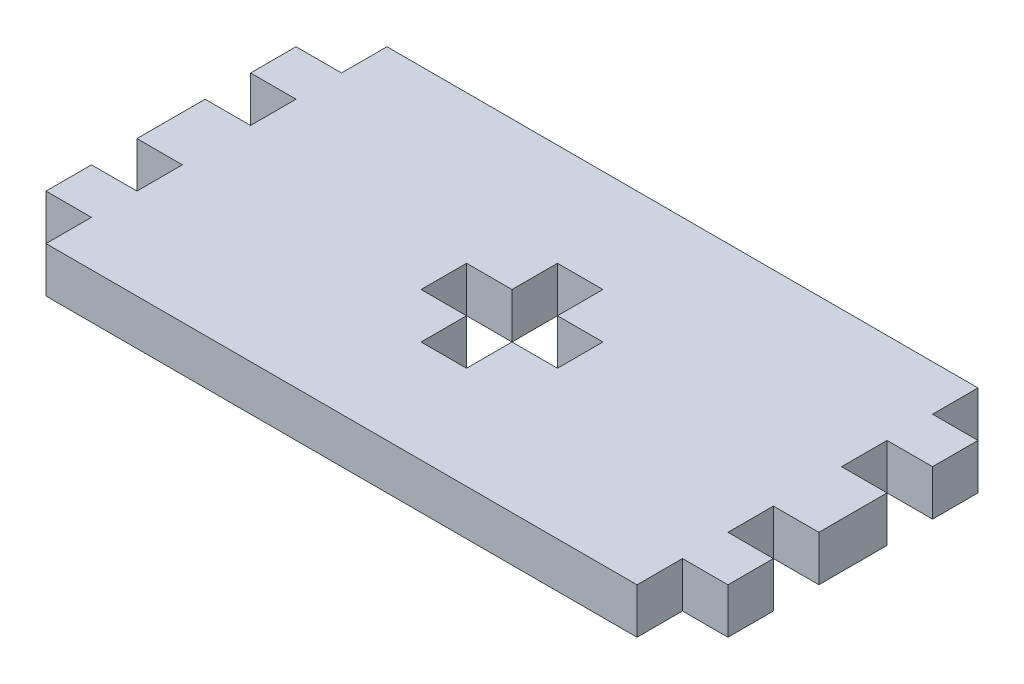
SolidWorks part; units mm, degrees
ref_plane "Front Plane" through (0, 0, 0) normal (0, 0, 1) x (1, 0, 0)
ref_plane "Top Plane" through (0, 0, 0) normal (0, 1, 0) x (1, 0, 0)
ref_plane "Right Plane" through (0, 0, 0) normal (1, 0, 0) x (0, 0, -1)
sketch "Sketch1" plane through (0, 0, 0) normal (0, 1, 0) x (1, 0, 0)
  line L1 (-38.7531, 31.6774) -> (37.4469, 31.6774)
  line L2 (-38.7531, 31.6774) -> (-38.7531, -6.4226)
  line L3 (-38.7531, -6.4226) -> (37.4469, -6.4226)
  line L4 (37.4469, 31.6774) -> (37.4469, -6.4226)
  dimension "D1" = 76.2
  dimension "D2" = 38.1
extrude "Boss-Extrude1" add sketch "Sketch1" along normal blind 5.08
sketch "Sketch2" plane through (0, 5.08, 0) normal (0, 1, 0) x (1, 0, 0)
  line L0 (-0.6531, 31.6774) -> (-0.6531, -6.4226) construction
  line L1 (37.4469, 31.6774) -> (-38.7531, 31.6774) construction
  line L2 (-38.7531, -6.4226) -> (37.4469, -6.4226) construction
  line L3 (-38.7531, 12.6274) -> (37.4469, 12.6274) construction
  line L4 (-38.7531, 31.6774) -> (-38.7531, -6.4226) construction
  line L5 (37.4469, -6.4226) -> (37.4469, 31.6774) construction
  line L6 (1.8869, 20.2474) -> (-3.1931, 20.2474)
  line L7 (-38.7531, 21.5174) -> (-33.6731, 21.5174)
  line L8 (-38.7531, 21.5174) -> (-38.7531, 16.4374)
  line L9 (-38.7531, 16.4374) -> (-33.6731, 16.4374)
  line L10 (-33.6731, 21.5174) -> (-33.6731, 16.4374)
  line L11 (-38.7531, 31.6774) -> (-33.6731, 31.6774)
  line L12 (-38.7531, 31.6774) -> (-38.7531, 26.5974)
  line L13 (-38.7531, 26.5974) -> (-33.6731, 26.5974)
  line L14 (-33.6731, 31.6774) -> (-33.6731, 26.5974)
  line L15 (-3.1931, 20.2474) -> (-3.1931, 15.1674)
  line L16 (-3.1931, 15.1674) -> (-8.2731, 15.1674)
  line L17 (-8.2731, 15.1674) -> (-8.2731, 10.0874)
  line L18 (-3.1931, 10.0874) -> (-8.2731, 10.0874)
  line L19 (-3.1931, 5.0074) -> (-3.1931, 10.0874)
  line L20 (-33.6731, -6.4226) -> (-33.6731, -1.3426)
  line L21 (-38.7531, -1.3426) -> (-33.6731, -1.3426)
  line L22 (-38.7531, -6.4226) -> (-38.7531, -1.3426)
  line L23 (-38.7531, -6.4226) -> (-33.6731, -6.4226)
  line L24 (-33.6731, 3.7374) -> (-33.6731, 8.8174)
  line L25 (-38.7531, 8.8174) -> (-33.6731, 8.8174)
  line L26 (-38.7531, 3.7374) -> (-38.7531, 8.8174)
  line L27 (-38.7531, 3.7374) -> (-33.6731, 3.7374)
  line L28 (1.8869, 5.0074) -> (-3.1931, 5.0074)
  line L29 (37.4469, 3.7374) -> (32.3669, 3.7374)
  line L30 (37.4469, 3.7374) -> (37.4469, 8.8174)
  line L31 (37.4469, 8.8174) -> (32.3669, 8.8174)
  line L32 (32.3669, 3.7374) -> (32.3669, 8.8174)
  line L33 (37.4469, -6.4226) -> (32.3669, -6.4226)
  line L34 (37.4469, -6.4226) -> (37.4469, -1.3426)
  line L35 (37.4469, -1.3426) -> (32.3669, -1.3426)
  line L36 (32.3669, -6.4226) -> (32.3669, -1.3426)
  line L37 (1.8869, 5.0074) -> (1.8869, 10.0874)
  line L38 (1.8869, 10.0874) -> (6.9669, 10.0874)
  line L39 (6.9669, 15.1674) -> (6.9669, 10.0874)
  line L40 (1.8869, 15.1674) -> (6.9669, 15.1674)
  line L41 (1.8869, 20.2474) -> (1.8869, 15.1674)
  line L42 (32.3669, 31.6774) -> (32.3669, 26.5974)
  line L43 (37.4469, 26.5974) -> (32.3669, 26.5974)
  line L44 (37.4469, 31.6774) -> (37.4469, 26.5974)
  line L45 (37.4469, 31.6774) -> (32.3669, 31.6774)
  line L46 (32.3669, 21.5174) -> (32.3669, 16.4374)
  line L47 (37.4469, 16.4374) -> (32.3669, 16.4374)
  line L48 (37.4469, 21.5174) -> (37.4469, 16.4374)
  line L49 (37.4469, 21.5174) -> (32.3669, 21.5174)
  point P26 (-8.2731, 12.6274)
  point P38 (-0.6531, 5.0074)
  point P39 (-0.6531, 20.2474)
  point P59 (6.9669, 12.6274)
  dimension "D1" = 3.81
  dimension "D2" = 5.08
  dimension "D3" = 5.08
  dimension "D4" = 5.08
  dimension "D5" = 5.08
  dimension "D6" = 5.08
  dimension "D7" = 2.54
  dimension "D8" = 2.54
  dimension "D9" = 5.08
  dimension "D10" = 5.08
extrude "Cut-Extrude1" cut sketch "Sketch2" against normal blind 5.08
